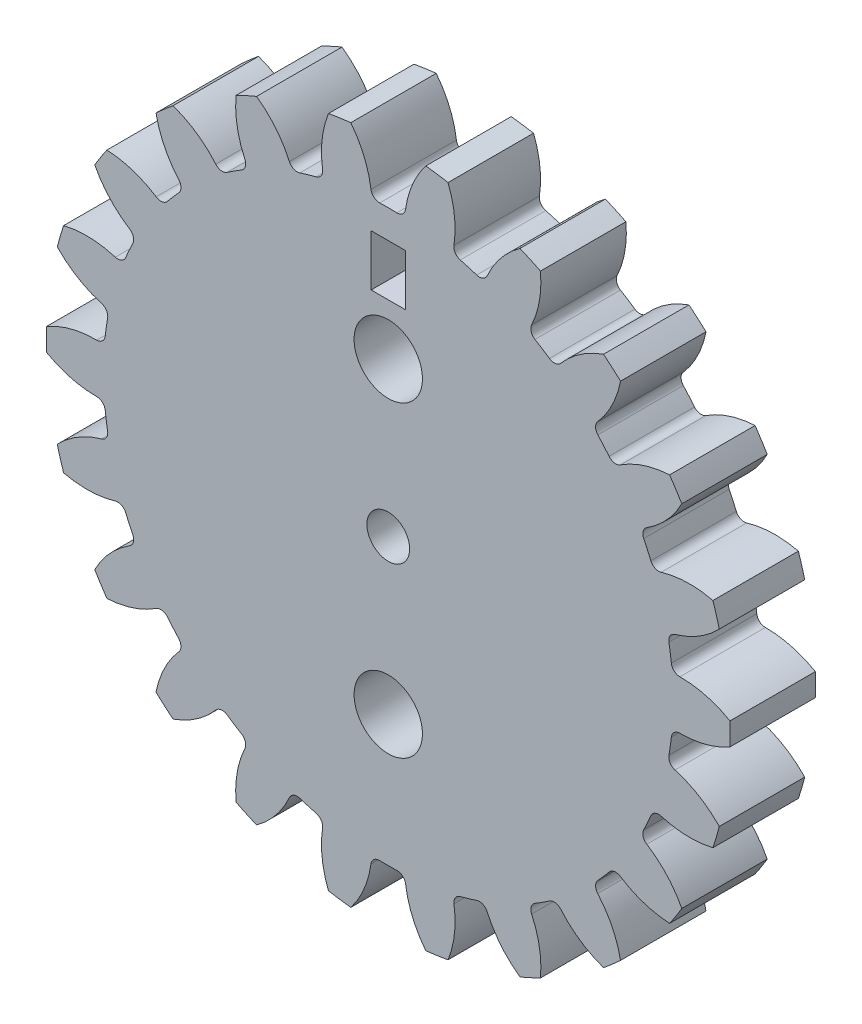
SolidWorks part; units mm, degrees
ref_plane "Front" through (0, 0, 0) normal (0, 0, 1) x (1, 0, 0)
ref_plane "Top" through (0, 0, 0) normal (0, 1, 0) x (1, 0, 0)
ref_plane "Right" through (0, 0, 0) normal (1, 0, 0) x (0, 0, -1)
sketch "Sketch1" plane through (0, 0, 0) normal (0, 0, 1) x (1, 0, 0)
  circle A0 centre (0, 0) radius 16.6667
  circle A1 centre (0, 0) radius 20
  circle A2 centre (0, 0) radius 18.3333
  dimension "D1" = 40
  dimension "D2" = 33.3333
  dimension "D3" = 36.6667
extrude "Boss-Extrude1" add sketch "Sketch1" along normal mid plane 5 contours A1
sketch "Sketch3" plane through (0, 0, 0) normal (0, 0, 1) x (1, 0, 0)
  line L0 (0, 0) -> (0, 20) construction
  line L1 (0, 0) -> (-0.9677, 16.6386) construction
  line L2 (-1.3079, 18.2866) -> (1.3079, 18.2866) construction
  line L3 (-1.8986, 19.9097) -> (0, 14.6932) construction
  line L4 (0, 0) -> (2.8463, 19.7964) construction
  line L5 (1.3079, 18.2866) -> (3.897, 17.9144) construction
  arc A0 (-0.9677, 16.6386) -> (0.9677, 16.6386) centre (0, 0) cw
  arc A4 (2.1919, 19.8795) -> (-2.1919, 19.8795) centre (0, 0) ccw
  circle A5 centre (0, 0) radius 20 construction
  arc A7 (-2.1919, 19.8795) -> (-0.9677, 16.6386) centre (-6.7617, 16.3016) cw
  arc A10 (2.1919, 19.8795) -> (0.9677, 16.6386) centre (6.7617, 16.3016) ccw
  circle A11 centre (0, 0) radius 16.6667 construction
  circle A12 centre (0, 0) radius 18.3333 construction
  dimension "D1" = 20
  dimension "D2" = 8.182
extrude "Cut-Extrude1" cut sketch "Sketch3" against normal through all both and the other way through all
fillet "Fillet2" radius 0.5 2 edges at (0.9677, 16.6386, 0) (-0.9677, 16.6386, 0)
pattern_circular "CirPattern1" count 22 over 360 about axis through (0, 0, 0) along (0, 0, 1) of "Cut-Extrude1", "Fillet2"
sketch "Sketch4" plane through (0, 0, 0) normal (0, 0, 1) x (1, 0, 0)
  circle A0 centre (0, 0) radius 1.25
  dimension "D1" = 2.5
extrude "String_Hole" cut sketch "Sketch4" against normal through all both and the other way through all
sketch "Sketch5" plane through (0, 0, 0) normal (0, 0, 1) x (1, 0, 0)
  line L0 (0, -9) -> (0, 9) construction
  circle A0 centre (0, 9) radius 2
  circle A1 centre (0, -9) radius 2
  point P5 (9, -8.8231)
  point P6 (-9, -6.5314)
  point P7 (0.6875, 12.9482)
  point P8 (-7.9637, -5.9012)
  dimension "D2" = 4
  dimension "D1" = 18
extrude "To_Knuckle_Mount" cut sketch "Sketch5" against normal through all both and the other way through all
sketch "Sketch7" plane through (0, 0, 2.5) normal (0, 0, 1) x (1, 0, 0)
  line L0 (0, 0) -> (0, 20) construction
  line L1 (-1, 12) -> (1, 12)
  line L2 (-1, 12) -> (-1, 15)
  line L3 (-1, 15) -> (1, 15)
  line L4 (1, 12) -> (1, 15)
  line L5 (-1, 12) -> (1, 15) construction
  line L6 (-1, 15) -> (1, 12) construction
  circle A0 centre (0, 9) radius 2 construction
  point P0 (0, 13.5)
  dimension "D1" = 2
  dimension "D2" = 3
  dimension "D3" = 3
extrude "For_Alignment" cut sketch "Sketch7" against normal blind 2
equation "\"od\"= 40'outside diameter"
equation "\"n\"= 22'number of teeth"
equation "\"m\"= \"od\" / ( \"n\" + 2 )'module"
equation "\"p\"= \"m\" * pi'pitch"
equation "\"d\"= \"m\" * \"n\"'primitive diameter"
equation "\"da\"= \"d\" + 2 * \"m\"'head diamater"
equation "\"df\"= \"d\" - 2 * \"m\"'foot diameter"
equation "\"D1@Sketch1\"=\"od\""
equation "\"D2@Sketch1\"=\"df\""
equation "\"D3@Sketch1\"=\"d\""
equation "\"D2@Sketch3\"=180/\"n\""
equation "\"D1@Fillet2\"=.3*\"m\""
equation "\"D1@CirPattern1\"=\"n\""
